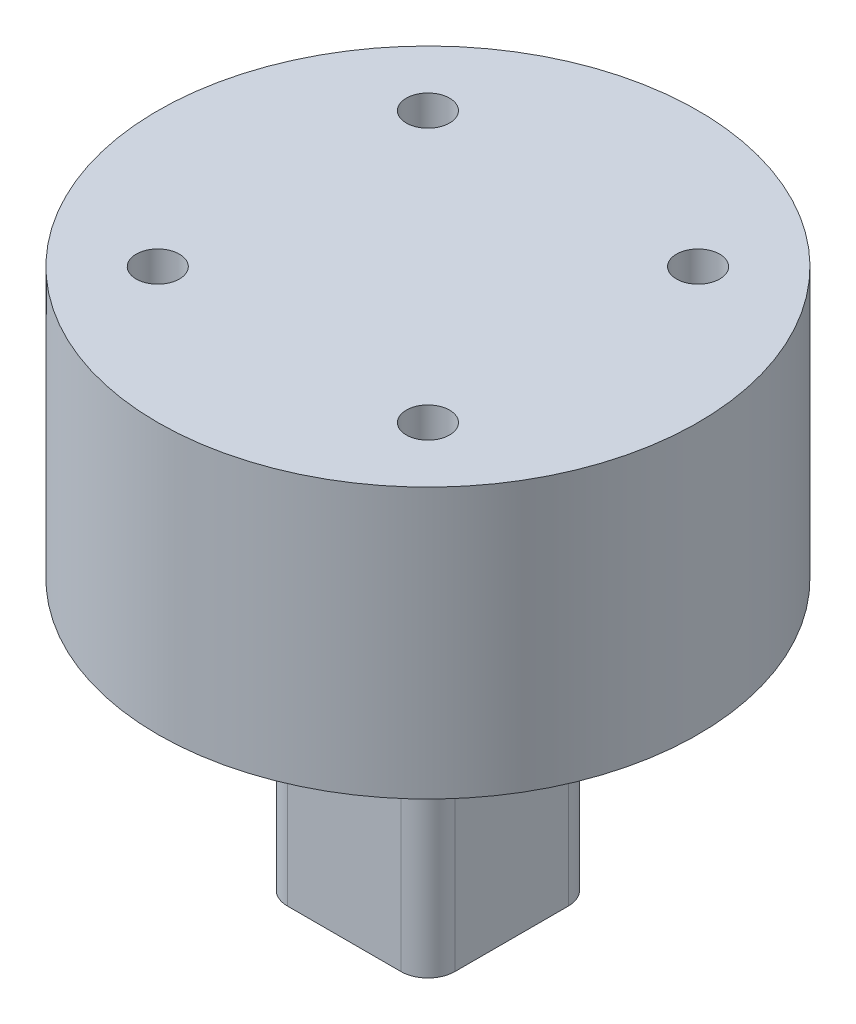
SolidWorks part; units mm, degrees
ref_plane "Front Plane" through (0, 0, 0) normal (0, 0, 1) x (1, 0, 0)
ref_plane "Top Plane" through (0, 0, 0) normal (0, 1, 0) x (1, 0, 0)
ref_plane "Right Plane" through (0, 0, 0) normal (1, 0, 0) x (0, 0, -1)
sketch "Sketch1" plane through (0, 0, 0) normal (0, 1, 0) x (1, 0, 0)
  circle A0 centre (0, 0) radius 10
  dimension "D1" = 20
extrude "Boss-Extrude1" add sketch "Sketch1" along normal blind 10
sketch "Sketch2" plane through (0, 10, 0) normal (0, 1, 0) x (1, 0, 0)
  line L1 (-5, 5) -> (5, 5) construction
  line L2 (-5, 5) -> (-5, -5) construction
  line L3 (-5, -5) -> (5, -5) construction
  line L4 (5, 5) -> (5, -5) construction
  line L5 (-5, 5) -> (5, -5) construction
  line L6 (-5, -5) -> (5, 5) construction
  point P0 (0, 0)
  dimension "D1" = 10
  dimension "D2" = 10
hole_wizard "M2x0.4 Tapped Hole1" positions "Sketch3" profile "Sketch4" tap size "M2x0.4" standard "ANSI Metric" end condition through all
sketch "Sketch3" plane through (0, 10, 0) normal (0, 1, 0) x (1, 0, 0)
  point P0 (-5, 5)
  point P3 (5, 5)
  point P6 (5, -5)
  point P9 (-5, -5)
sketch "Sketch4" plane through (-5, 10, -5) normal (1, 0, 0) x (0, 0, 1)
  line L0 (0, 0) -> (0, 10)
  line L1 (0, 10) -> (0.8, 10)
  line L2 (0.8, 10) -> (0.8, 0)
  line L5 (0.8, 0) -> (0, 0)
  line L11 (0, -6.35) -> (0, 107.95) construction
  dimension "Thru Tap Drill Dia." = 1.6
  dimension "Thru Tap Drill Depth" = 10
cosmetic thread "Hole Thread1" parameters "D2"=2
cosmetic thread "Hole Thread2" parameters "D2"=2
cosmetic thread "Hole Thread3" parameters "D2"=2
cosmetic thread "Hole Thread4" parameters "D2"=2
sketch "Sketch5" plane through (0, 0, 0) normal (0, -1, 0) x (1, 0, 0)
  line L1 (-2.1, 3.1) -> (2.1, 3.1)
  line L2 (-3.1, 2.1) -> (-3.1, -2.1)
  line L3 (-2.1, -3.1) -> (2.1, -3.1)
  line L4 (3.1, 2.1) -> (3.1, -2.1)
  line L5 (-3.1, 3.1) -> (3.1, -3.1) construction
  line L6 (-3.1, -3.1) -> (3.1, 3.1) construction
  arc A0 (-2.1, -3.1) -> (-3.1, -2.1) centre (-2.1, -2.1) cw
  arc A1 (3.1, -2.1) -> (2.1, -3.1) centre (2.1, -2.1) cw
  arc A2 (3.1, 2.1) -> (2.1, 3.1) centre (2.1, 2.1) ccw
  arc A3 (-3.1, 2.1) -> (-2.1, 3.1) centre (-2.1, 2.1) cw
  point P0 (0, 0)
  dimension "D3" = 1
  dimension "D1" = 6.2
  dimension "D2" = 6.2
extrude "Boss-Extrude2" add sketch "Sketch5" along normal blind 10
